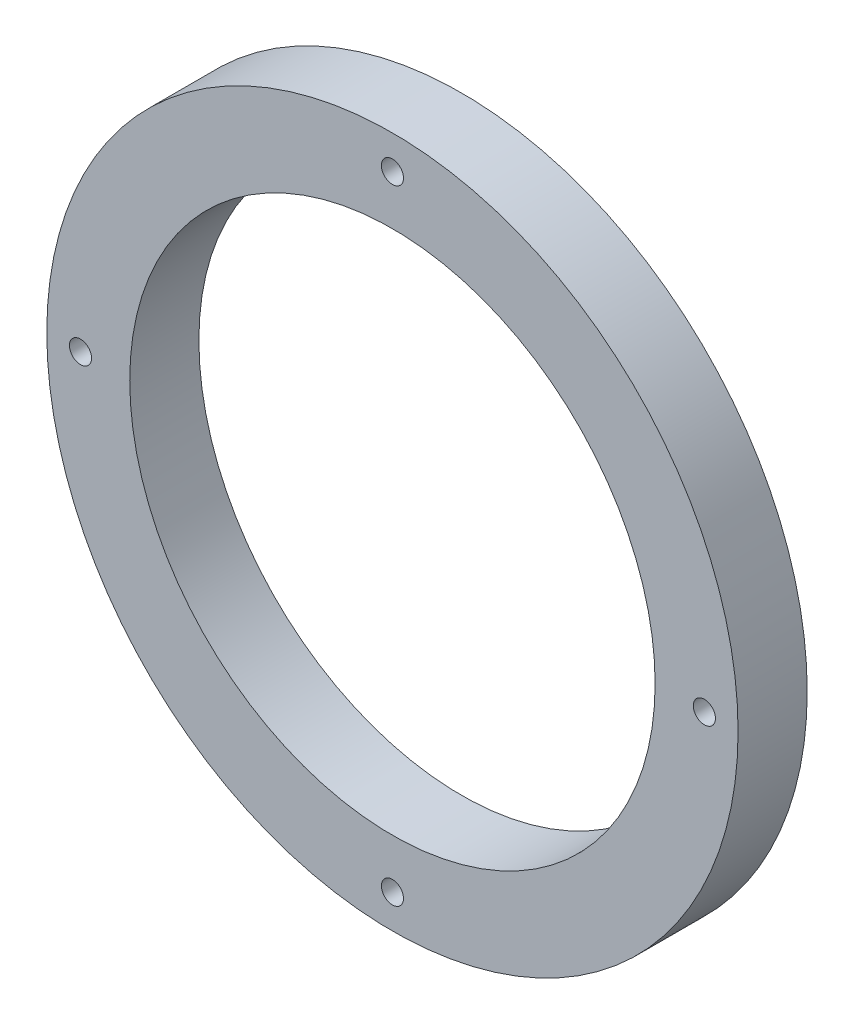
SolidWorks part; units mm, degrees
ref_plane "Front Plane" through (0, 0, 0) normal (0, 0, 1) x (1, 0, 0)
ref_plane "Top Plane" through (0, 0, 0) normal (0, 1, 0) x (1, 0, 0)
ref_plane "Right Plane" through (0, 0, 0) normal (1, 0, 0) x (0, 0, -1)
sketch "Sketch1" plane through (0, 0, 0) normal (0, 0, 1) x (1, 0, 0)
  circle A0 centre (0, 0) radius 50
  circle A1 centre (0, 0) radius 38
  circle A2 centre (0, 45.125) radius 1.6
  circle A3 centre (45.125, 0) radius 1.6
  circle A4 centre (0, -45.125) radius 1.6
  circle A5 centre (-45.125, 0) radius 1.6
  point P15 (0, 0)
  dimension "D1" = 100
  dimension "D2" = 76
  dimension "D3" = 3.2
  dimension "D4" = 45.125
  dimension "D5" = 4
extrude "Boss-Extrude1" add sketch "Sketch1" along normal blind 10
